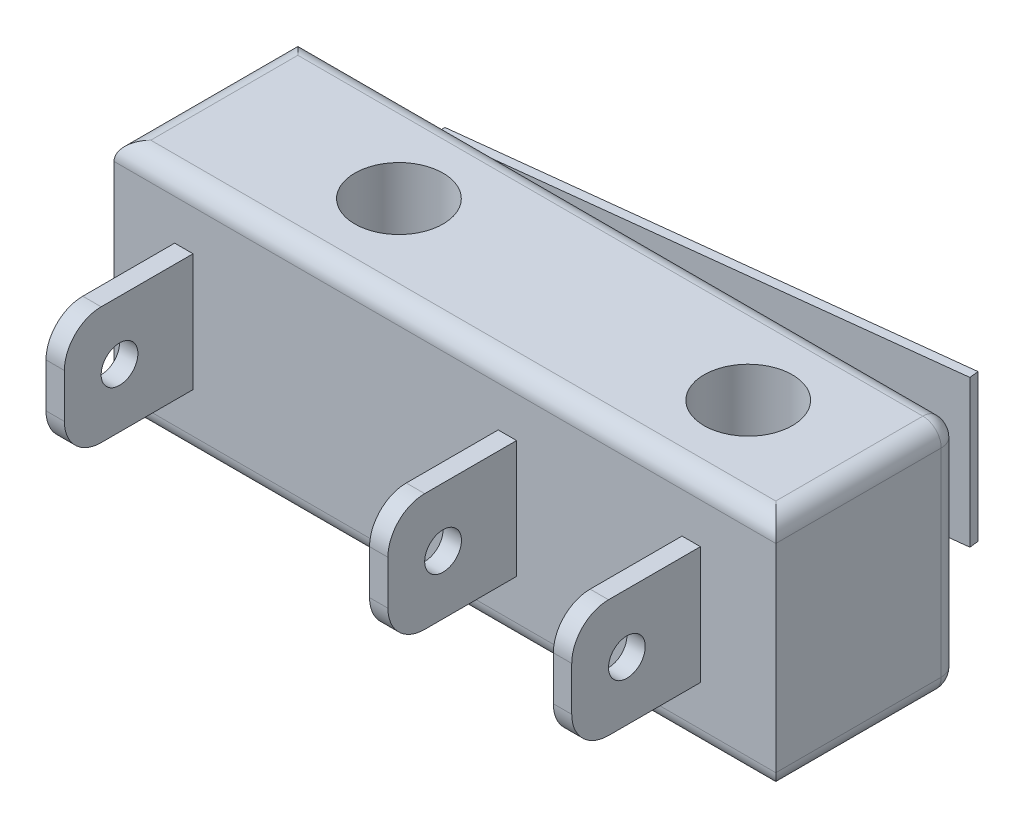
SolidWorks part; units mm, degrees
ref_plane "Front Plane" through (0, 0, 0) normal (0, 0, 1) x (1, 0, 0)
ref_plane "Top Plane" through (0, 0, 0) normal (0, 1, 0) x (1, 0, 0)
ref_plane "Right Plane" through (0, 0, 0) normal (1, 0, 0) x (0, 0, -1)
sketch "Sketch1" plane through (0, 0, 0) normal (0, 1, 0) x (1, 0, 0)
  line L0 (5.25, 2.5) -> (14.75, 2.5) construction
  line L1 (0, 0) -> (18, 0)
  line L2 (0, 0) -> (0, 5)
  line L3 (0, 5) -> (18, 5)
  line L4 (18, 0) -> (18, 5)
  circle A0 centre (5.25, 2.5) radius 1.2
  circle A1 centre (14.75, 2.5) radius 1.2
  dimension "D5" = 2.4
  dimension "D1" = 18
  dimension "D2" = 5
  dimension "D3" = 9.5
  dimension "D4" = 5.25
  dimension "D6" = 2.5
extrude "Boss-Extrude1" add sketch "Sketch1" along normal blind 6.4
sketch "Sketch2" plane through (0, 0, 0) normal (0, 0, 1) x (1, 0, 0)
  line L0 (1.9, 6.4) -> (1.9, 0) construction
  line L1 (0, 6.4) -> (18, 6.4) construction
  line L2 (0, 0) -> (18, 0) construction
  line L3 (10.7, 6.4) -> (10.7, 0) construction
  line L4 (15.7, 6.4) -> (15.7, 0) construction
  line L5 (0, 6.4) -> (0, 0) construction
  line L6 (15.95, 4.8) -> (15.45, 4.8)
  line L7 (15.95, 4.8) -> (15.95, 1.6)
  line L8 (15.95, 1.6) -> (15.45, 1.6)
  line L9 (15.45, 4.8) -> (15.45, 1.6)
  line L10 (15.95, 4.8) -> (15.45, 1.6) construction
  line L11 (15.95, 1.6) -> (15.45, 4.8) construction
  line L12 (10.45, 4.8) -> (10.95, 4.8)
  line L13 (10.45, 4.8) -> (10.45, 1.6)
  line L14 (10.45, 1.6) -> (10.95, 1.6)
  line L15 (10.95, 4.8) -> (10.95, 1.6)
  line L16 (10.45, 4.8) -> (10.95, 1.6) construction
  line L17 (10.45, 1.6) -> (10.95, 4.8) construction
  line L18 (1.65, 4.8) -> (2.15, 4.8)
  line L19 (1.65, 4.8) -> (1.65, 1.6)
  line L20 (1.65, 1.6) -> (2.15, 1.6)
  line L21 (2.15, 4.8) -> (2.15, 1.6)
  line L22 (1.65, 4.8) -> (2.15, 1.6) construction
  line L23 (1.65, 1.6) -> (2.15, 4.8) construction
  point P10 (15.7, 3.2)
  point P15 (10.7, 3.2)
  point P20 (1.9, 3.2)
  dimension "D1" = 1.9
  dimension "D2" = 8.8
  dimension "D3" = 5
  dimension "D4" = 3.2
  dimension "D5" = 0.5
extrude "Boss-Extrude2" add sketch "Sketch2" along normal blind 3.5
sketch "Sketch3" plane through (1.65, 0, 0) normal (-1, 0, 0) x (0, 0, 1)
  line L0 (3.5, 3.2) -> (0, 3.2) construction
  line L1 (3.5, 4.8) -> (3.5, 1.6) construction
  line L2 (0, 4.8) -> (0, 1.6) construction
  circle A0 centre (2, 3.2) radius 0.5
  dimension "D1" = 1
  dimension "D2" = 1.5
extrude "Cut-Extrude1" cut sketch "Sketch3" against normal through all
fillet "Fillet1" radius 1 6 edges at (15.7, 1.6, 3.5) (15.7, 4.8, 3.5) (10.7, 4.8, 3.5) (10.7, 1.6, 3.5) (1.9, 1.6, 3.5) (1.9, 4.8, 3.5)
fillet "Fillet2" radius 0.5 9 edges at (9, 0, -5) (9, 6.4, -5) (18, 3.2, -5) (18, 0, -2.5) (18, 6.4, -2.5) (0, 0, -2.5) (0, 6.4, -2.5) (9, 0, 0) (9, 6.4, 0)
ref_plane "Plane1" through (0, 3.2, 0) normal (0, 1, 0) x (1, 0, 0)
sketch "Sketch4" plane through (0, 3.2, 0) normal (0, 1, 0) x (1, 0, 0)
  line L0 (3, 5) -> (3, 6)
  line L1 (0, 5) -> (17.5, 5) construction
  line L2 (3, 6) -> (16, 7.5)
  line L3 (0, 0) -> (0, 5) construction
  circle A0 centre (14.75, 2.5) radius 1.2 construction
  dimension "D2" = 5
  dimension "D1" = 13
  dimension "D3" = 1
  dimension "D4" = 3
extrude "Extrude-Thin2" add sketch "Sketch4" against normal blind 2 and the other way blind 2 thin
sketch "Sketch5" plane through (0, 3.2, 0) normal (0, 1, 0) x (1, 0, 0)
  line L0 (4.75, 5) -> (4.75, 5.2818)
  line L1 (6.25, 5.2818) -> (6.25, 5)
  line L2 (0, 5) -> (17.5, 5) construction
  line L3 (3.25, 5.7772) -> (16.0287, 7.2516) construction
  line L4 (3.25, 5) -> (3.25, 5.7772) construction
  line L5 (6.25, 5) -> (4.75, 5)
  arc A0 (4.75, 5.2818) -> (6.25, 5.2818) centre (5.5, 5.2818) cw
  point P9 (3.25, 5.3886)
  dimension "D1" = 1.5
  dimension "D2" = 1.5
extrude "Boss-Extrude6" add sketch "Sketch5" along normal blind 0.5 and the other way blind 0.5 separate body
